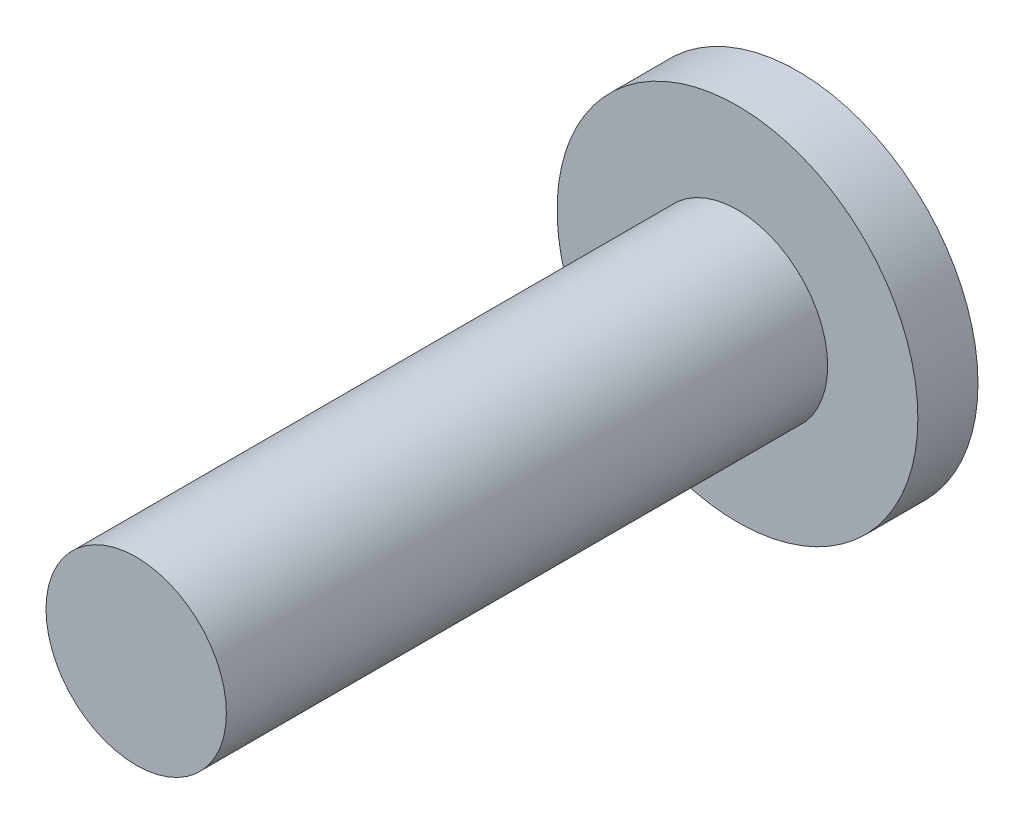
SolidWorks part; units mm, degrees
ref_plane "前视基准面" through (0, 0, 0) normal (0, 0, 1) x (1, 0, 0)
ref_plane "上视基准面" through (0, 0, 0) normal (0, 1, 0) x (1, 0, 0)
ref_plane "右视基准面" through (0, 0, 0) normal (1, 0, 0) x (0, 0, -1)
sketch "草图1" plane through (0, 0, 0) normal (0, 0, 1) x (1, 0, 0)
  circle A0 centre (0, 0) radius 3
extrude "凸台-拉伸1" add sketch "草图1" along normal blind 1
sketch "草图2" plane through (0, 0, 1) normal (0, 0, 1) x (1, 0, 0)
  circle A0 centre (0, 0) radius 1.5
extrude "凸台-拉伸2" add sketch "草图2" along normal blind 10
